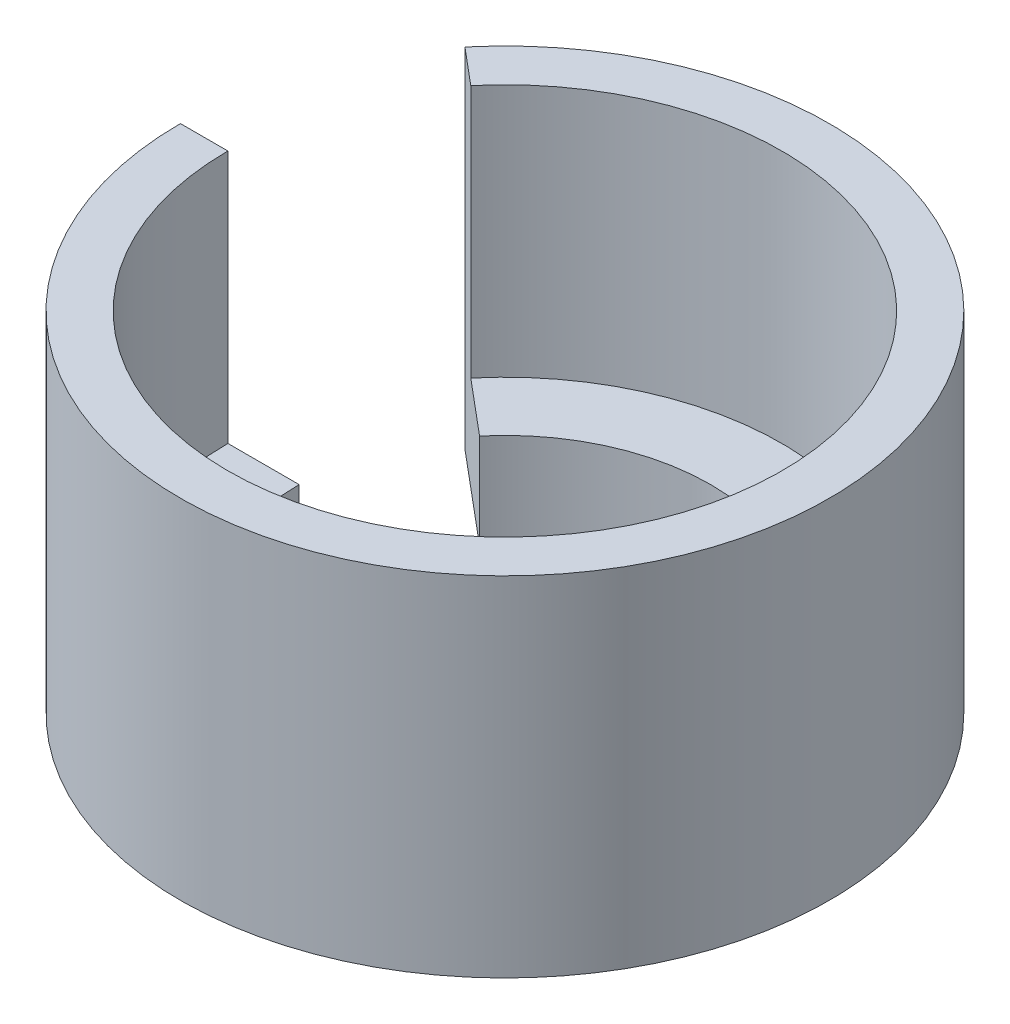
SolidWorks part; units mm, degrees
material "Custom Plastic"
ref_plane "Front Plane" through (0, 0, 0) normal (0, 0, 1) x (1, 0, 0)
ref_plane "Top Plane" through (0, 0, 0) normal (0, 1, 0) x (1, 0, 0)
ref_plane "Right Plane" through (0, 0, 0) normal (1, 0, 0) x (0, 0, -1)
sketch "Sketch1" plane through (0, 0, 0) normal (0, 0, 1) x (1, 0, 0)
  line L0 (0, 0) -> (0, 16.4642) construction
  line L1 (-3.5, 1.2) -> (-3.5, 4.4)
  line L2 (-3.5, 4.4) -> (-4.1, 4.4)
  line L3 (-4.1, 4.4) -> (-4.1, 0)
  line L6 (-3.5, 1.2) -> (-2.6, 1.2)
  line L8 (-4.1, 0) -> (-2.6, 0)
  line L9 (-2.6, 1.2) -> (-2.6, 0)
  dimension "D1" = 0.6
  dimension "D2" = 7
  dimension "D3" = 3.2
  dimension "D4" = 1.2
  dimension "D5" = 5.2
revolve "Revolve1" add sketch "Sketch1" angle 320 about L0
